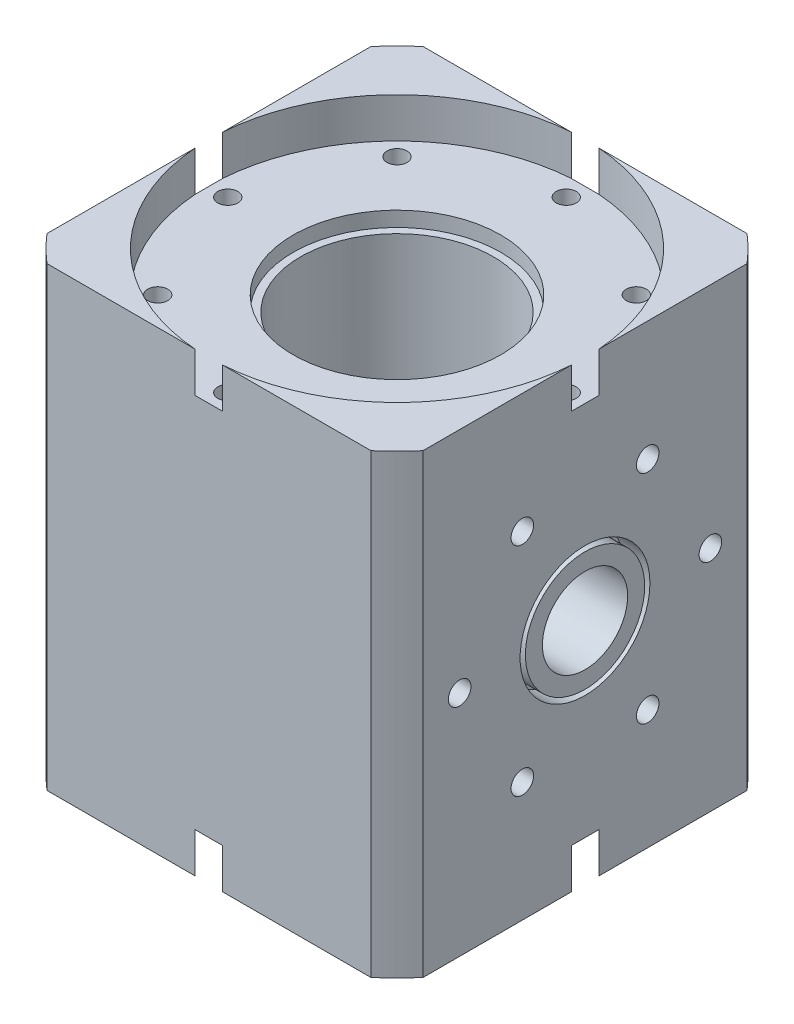
SolidWorks part; units mm, degrees
material "Alumina"
ref_plane "Front Plane" through (0, 0, 0) normal (0, 0, 1) x (1, 0, 0)
ref_plane "Top Plane" through (0, 0, 0) normal (0, 1, 0) x (1, 0, 0)
ref_plane "Right Plane" through (0, 0, 0) normal (1, 0, 0) x (0, 0, -1)
sketch "Sketch1" plane through (0, 0, 0) normal (0, 1, 0) x (1, 0, 0)
  line L0 (-37.5, -37.5) -> (37.5, -37.5)
  line L1 (-37.5, -37.5) -> (-37.5, 37.5)
  line L2 (37.5, -37.5) -> (37.5, 37.5)
  line L3 (-37.5, 37.5) -> (37.5, 37.5)
  line L4 (-37.5, -37.5) -> (37.5, 37.5) construction
  line L5 (37.5, -37.5) -> (-37.5, 37.5) construction
  point P1 (0, 0)
  dimension "D1" = 75
  dimension "D2" = 75
extrude "Boss-Extrude1" add sketch "Sketch1" along normal blind 75
sketch "Sketch2" plane through (0, 0, 0) normal (0, -1, 0) x (-1, 0, 0)
  circle A0 centre (0, 0) radius 5.35
  dimension "D1" = 10.7
extrude "Cut-Extrude1" cut sketch "Sketch2" against normal through all
sketch "Sketch5" plane through (37.5, 0, 0) normal (1, 0, 0) x (0, 0, -1)
  line L0 (0, 0) -> (0, 75) construction
  line L1 (-37.5, 0) -> (37.5, 0) construction
  line L2 (-37.5, 75) -> (37.5, 75) construction
  line L3 (-37.5, 37.5) -> (37.5, 37.5) construction
  line L4 (-37.5, 75) -> (-37.5, 0) construction
  line L5 (37.5, 75) -> (37.5, 0) construction
  circle A0 centre (0, 37.5) radius 8.5
  dimension "D1" = 17
extrude "Cut-Extrude2" cut sketch "Sketch5" against normal through all
sketch "Sketch7" plane through (0, 0, 0) normal (0, -1, 0) x (1, 0, 0)
  circle A0 centre (0, 0) radius 19.21
  circle A1 centre (0, 0) radius 20.71
  dimension "D1" = 38.42
  dimension "D2" = 41.42
extrude "Cut-Extrude3" cut sketch "Sketch7" against normal blind 3
sketch "Sketch8" plane through (0, 0, 0) normal (0, -1, 0) x (1, 0, 0)
  line L4 (-37.5, 37.5) -> (-37.5, -37.5)
  line L5 (-37.5, -37.5) -> (37.5, -37.5)
  line L6 (37.5, -37.5) -> (37.5, 37.5)
  line L7 (37.5, 37.5) -> (-37.5, 37.5)
  line L8 (-37.5, 37.5) -> (-37.5, -37.5)
  line L9 (-37.5, -37.5) -> (37.5, -37.5)
  line L10 (37.5, -37.5) -> (37.5, 37.5)
  line L11 (37.5, 37.5) -> (-37.5, 37.5)
  circle A0 centre (0, 0) radius 20.71 construction
  circle A1 centre (0, 0) radius 20.71
  circle A2 centre (0, 0) radius 30
  dimension "D2" = 37.5
  dimension "D3" = 41.42
  dimension "D4" = 60
  dimension "D1" = 0
sketch "Sketch11" plane through (0, 0, 0) normal (0, -1, 0) x (1, 0, 0)
  line L0 (-37.5, 37.5) -> (-37.5, -37.5) construction
  circle A0 centre (-33.75, 0) radius 2
  circle A1 centre (-23.8649, 23.8649) radius 2
  circle A2 centre (0, 33.75) radius 2
  circle A3 centre (23.8649, 23.8649) radius 2
  circle A4 centre (33.75, 0) radius 2
  circle A5 centre (23.8649, -23.8649) radius 2
  circle A6 centre (0, -33.75) radius 2
  circle A7 centre (-23.8649, -23.8649) radius 2
  point P16 (0, 0)
  dimension "D1" = 4
  dimension "D2" = 3.75
  dimension "D3" = 8
extrude "Cut-Extrude4" cut sketch "Sketch11" against normal blind 10
ref_plane "Plane1" through (0, 37.5, 0) normal (0, 1, 0) x (1, 0, 0)
mirror "Mirror1" about plane through (0, 37.5, 0) normal (0, 1, 0) of "Cut-Extrude3", "Cut-Extrude4"
sketch "Sketch14" plane through (0, 0, 0) normal (0, -1, 0) x (1, 0, 0)
  circle A0 centre (0, 0) radius 37.5
sketch "Sketch12" plane through (0, 0, 0) normal (0, -1, 0) x (1, 0, 0)
  circle A2 centre (0, 0) radius 42.5
  circle A3 centre (0, 0) radius 42.5
  dimension "D1" = 5
extrude "Cut-Extrude6" [suppressed] cut sketch "Sketch12" against normal through all flip side to cut
sketch "Sketch13" plane through (0, 75, 0) normal (0, 1, 0) x (1, 0, 0)
  circle A0 centre (0, 0) radius 19.21 construction
  circle A1 centre (0, 0) radius 19.21
extrude "Cut-Extrude7" cut sketch "Sketch13" against normal blind 50
sketch "Sketch15" [suppressed] plane through (0, 0, -37.5) normal (0, 0, -1) x (-1, 0, 0)
  line L0 (-20, 5) -> (20, 5) construction
  line L1 (-20, 0) -> (-20, 75) construction
  line L2 (20, 75) -> (20, 0) construction
  line L3 (-20, 0) -> (20, 0) construction
  text T0 "IISER M" font "Consolas" height 3.5
  dimension "D1" = 5
sketch "Sketch16" plane through (0, 0, 0) normal (0, 1, 0) x (1, 0, 0)
  circle A1 centre (0, 0) radius 37.5
  circle A2 centre (0, 0) radius 37.5
  dimension "D1" = 0
ref_plane "Plane2" through (37.5, 0, 0) normal (1, 0, 0) x (0, 0, -1)
sketch "Sketch19" plane through (37.5, 0, 0) normal (1, 0, 0) x (0, 0, -1)
  circle A1 centre (0, 37.5) radius 11.9
  circle A2 centre (0, 37.5) radius 12.95
  circle A3 centre (0, 37.5) radius 20 construction
  dimension "D1" = 23.8
  dimension "D2" = 25.9
  dimension "D3" = 40
extrude "Cut-Extrude9" cut sketch "Sketch19" against normal blind 5
sketch "Sketch20" plane through (37.5, 0, 0) normal (1, 0, 0) x (0, 0, -1)
  circle A0 centre (-25, 37.5) radius 2.25
  circle A1 centre (0, 37.5) radius 20 construction
  circle A2 centre (-12.5, 59.1506) radius 2.25
  circle A3 centre (12.5, 59.1506) radius 2.25
  circle A4 centre (25, 37.5) radius 2.25
  circle A5 centre (12.5, 15.8494) radius 2.25
  circle A6 centre (-12.5, 15.8494) radius 2.25
  point P17 (0, 37.5)
  dimension "D1" = 40
  dimension "D2" = 4.5
  dimension "D3" = 25
  dimension "D4" = 6
extrude "Cut-Extrude10" cut sketch "Sketch20" against normal blind 12.7
ref_plane "Plane3" through (0, 0, 0) normal (-1, 0, 0) x (0, 0, 1)
mirror "Mirror4" about plane through (0, 0, 0) normal (-1, 0, 0) of "Cut-Extrude10", "Cut-Extrude9"
sketch "Sketch25" plane through (0, 0, 0) normal (0, 1, 0) x (1, 0, 0)
  line L0 (-37.5, 37.5) -> (-37.5, 2.7404)
  line L1 (-2.7404, 37.5) -> (-37.5, 37.5)
  line L2 (37.5, 37.5) -> (2.7404, 37.5)
  line L3 (37.5, 2.7404) -> (37.5, 37.5)
  line L4 (-37.5, -37.5) -> (37.5, -37.5)
  line L5 (37.5, -37.5) -> (37.5, 37.5)
  line L6 (37.5, 37.5) -> (-37.5, 37.5)
  line L7 (-37.5, 37.5) -> (-37.5, -37.5)
  line L8 (-37.5, -37.5) -> (-2.7404, -37.5)
  line L9 (37.5, -37.5) -> (37.5, -2.7404)
  line L10 (2.7404, -37.5) -> (37.5, -37.5)
  line L11 (-37.5, -2.7404) -> (-37.5, -37.5)
  arc A1 (-2.7404, 37.5) -> (-37.5, 2.7404) centre (0, 0) ccw
  circle A2 centre (0, 0) radius 37.6
  arc A3 (-37.5, -2.7404) -> (-2.7404, -37.5) centre (0, 0) ccw
  arc A4 (37.5, 2.7404) -> (2.7404, 37.5) centre (0, 0) ccw
  arc A5 (2.7404, -37.5) -> (37.5, -2.7404) centre (0, 0) ccw
  point P20 (0, 0)
  dimension "D1" = 0.1
  dimension "D2" = 0
extrude "Boss-Extrude2" add sketch "Sketch25" against normal blind 8
ref_plane "Plane4" through (0, 37.5, 0) normal (0, -1, 0) x (-1, 0, 0)
mirror "Mirror5" about plane through (0, 37.5, 0) normal (0, -1, 0) of "Boss-Extrude2"
sketch "Sketch24" plane through (0, 0, 0) normal (0, 1, 0) x (1, 0, 0)
  circle A2 centre (0, 0) radius 49.5
  circle A3 centre (0, 0) radius 49.5
  dimension "D1" = 12
extrude "Cut-Extrude14" cut sketch "Sketch24" against normal through all and the other way through all flip side to cut
